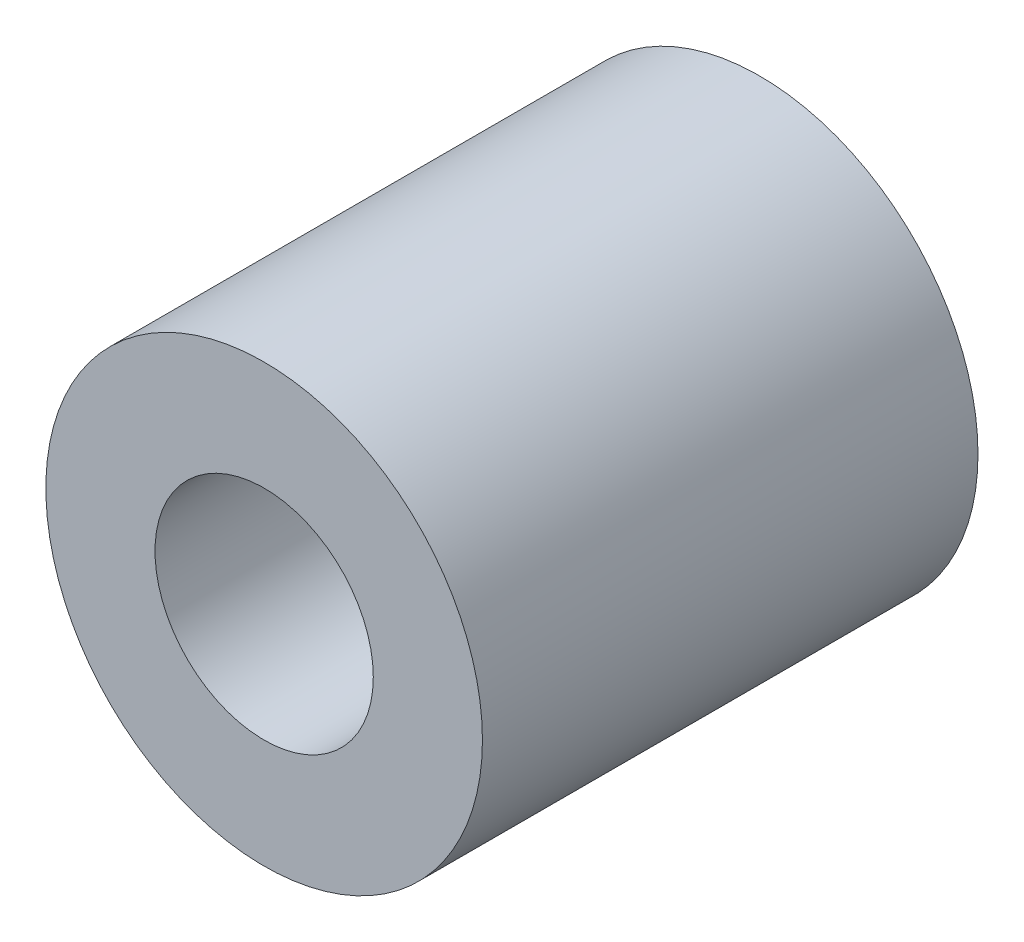
SolidWorks part; units mm, degrees
ref_plane "정면" through (0, 0, 0) normal (0, 0, 1) x (1, 0, 0)
ref_plane "윗면" through (0, 0, 0) normal (0, 1, 0) x (1, 0, 0)
ref_plane "우측면" through (0, 0, 0) normal (1, 0, 0) x (0, 0, -1)
sketch "스케치1" plane through (0, 0, 0) normal (0, 0, 1) x (1, 0, 0)
  circle A0 centre (0, 0) radius 5
  circle A1 centre (0, 0) radius 2.5
  dimension "D1" = 10
  dimension "D2" = 5
extrude "보스-돌출1" add sketch "스케치1" along normal blind 11.35
